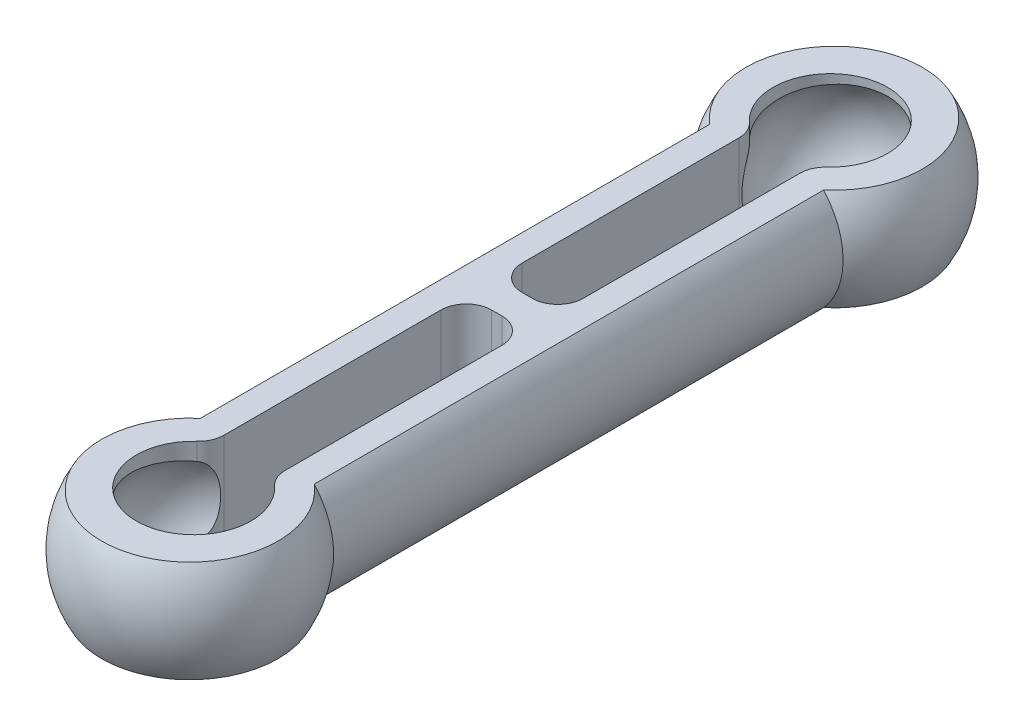
SolidWorks part; units mm, degrees
ref_plane "Front Plane" through (0, 0, 0) normal (0, 0, 1) x (1, 0, 0)
ref_plane "Top Plane" through (0, 0, 0) normal (0, 1, 0) x (1, 0, 0)
ref_plane "Right Plane" through (0, 0, 0) normal (1, 0, 0) x (0, 0, -1)
sketch "Sketch1" plane through (0, 0, 0) normal (0, 1, 0) x (1, 0, 0)
  line L0 (0, 91.3941) -> (0, -96.7552) construction
  line L1 (-73.1408, 0) -> (76.2043, 0) construction
  line L2 (-3, -10) -> (-3, 10)
  line L6 (0, -8.6458) -> (0, 8.6458)
  line L7 (0, 8.6458) -> (0, 9.9458)
  line L8 (0, -8.6458) -> (0, -9.9458)
  line L9 (0, 15.3458) -> (0, 16.6458)
  line L10 (0, -15.3458) -> (0, -16.6458)
  arc A0 (0, 16.6458) -> (-3, 10) centre (0, 12.6458) ccw
  arc A2 (0, -16.6458) -> (-3, -10) centre (0, -12.6458) cw
  arc A3 (0, 15.3458) -> (0, 9.9458) centre (0, 12.6458) ccw
  arc A4 (0, -9.9458) -> (0, -15.3458) centre (0, -12.6458) ccw
  dimension "D5" = 4
  dimension "D6" = 5.4
  dimension "D7" = 5.4
  dimension "D1" = 3
  dimension "D2" = 8
  dimension "D3" = 20
  dimension "D4" = 3
revolve "Revolve1" add sketch "Sketch1" angle 360 about L0
sketch "Sketch2" plane through (0, 0, 0) normal (0, 1, 0) x (1, 0, 0)
  line L0 (0, 0) -> (0, 74.3344) construction
  line L1 (0, 0) -> (0, -69.9604) construction
  line L2 (-1.2, 10.1078) -> (-1.2, 1.5967)
  line L3 (-0.2, 0.5967) -> (0.2, 0.5967)
  line L4 (1.2, 1.5967) -> (1.2, 10.1078)
  line L5 (0, 0) -> (14.3556, 0) construction
  line L6 (-1.2, -10.1078) -> (-1.2, -1.5967)
  line L7 (-0.2, -0.5967) -> (0.2, -0.5967)
  line L8 (1.2, -1.5967) -> (1.2, -10.1078)
  arc A0 (1.5231, 10.8439) -> (-1.5231, 10.8439) centre (0, 12.5) ccw
  arc A2 (1.5231, -10.8439) -> (-1.5231, -10.8439) centre (0, -12.5) cw
  arc A3 (-1.2, 10.1078) -> (-1.5231, 10.8439) centre (-2.2, 10.1078) ccw
  arc A4 (1.2, 10.1078) -> (1.5231, 10.8439) centre (2.2, 10.1078) cw
  arc A5 (-1.2, 1.5967) -> (-0.2, 0.5967) centre (-0.2, 1.5967) ccw
  arc A6 (0.2, 0.5967) -> (1.2, 1.5967) centre (0.2, 1.5967) ccw
  arc A7 (-1.5231, -10.8439) -> (-1.2, -10.1078) centre (-2.2, -10.1078) ccw
  arc A8 (1.5231, -10.8439) -> (1.2, -10.1078) centre (2.2, -10.1078) cw
  arc A9 (0.2, -0.5967) -> (1.2, -1.5967) centre (0.2, -1.5967) cw
  arc A10 (-1.2, -1.5967) -> (-0.2, -0.5967) centre (-0.2, -1.5967) cw
  point P17 (-1.2, 10.5967)
  point P20 (1.2, 10.5967)
  point P23 (-1.2, 0.5967)
  point P26 (1.2, 0.5967)
  point P29 (-1.2, -10.5967)
  point P32 (1.2, -10.5967)
  point P35 (1.2, -0.5967)
  point P38 (-1.2, -0.5967)
  dimension "D1" = 4.5
  dimension "D3" = 1
  dimension "D2" = 12.5
  dimension "D5" = 1.2
  dimension "D6" = 1.2
  dimension "D7" = 10
extrude "Cut-Extrude1" cut sketch "Sketch2" against normal mid plane 60
sketch "Sketch3" plane through (0, 0, 0) normal (1, 0, 0) x (0, 0, -1)
  line L0 (0, -2) -> (70.025, -2)
  line L1 (70.025, -2) -> (70.025, -4)
  line L2 (70.025, -4) -> (-79.975, -4)
  line L3 (-79.975, -4) -> (-79.975, -2)
  line L4 (-79.975, -2) -> (0, -2)
  line L5 (73.071, 0) -> (-75.6054, 0) construction
  line L6 (0, 2) -> (70.025, 2)
  line L7 (-79.975, 2) -> (0, 2)
  line L8 (-79.975, 4) -> (-79.975, 2)
  line L9 (70.025, 4) -> (-79.975, 4)
  line L10 (70.025, 4) -> (70.025, 2)
  dimension "D1" = 2
  dimension "D2" = 2
  dimension "D3" = 150
  dimension "D4" = 80
extrude "Cut-Extrude2" cut sketch "Sketch3" against normal mid plane 60
